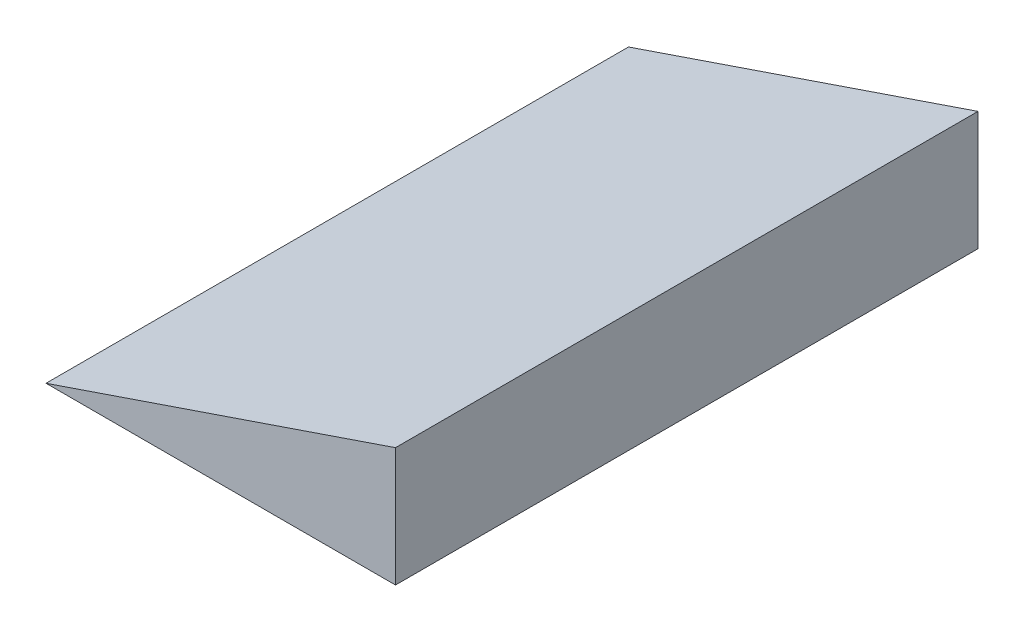
SolidWorks part; units mm, degrees
ref_plane "Front Plane" through (0, 0, 0) normal (0, 0, 1) x (1, 0, 0)
ref_plane "Top Plane" through (0, 0, 0) normal (0, 1, 0) x (1, 0, 0)
ref_plane "Right Plane" through (0, 0, 0) normal (1, 0, 0) x (0, 0, -1)
sketch "Sketch1" plane through (0, 0, 0) normal (0, 0, 1) x (1, 0, 0)
  line L0 (0, 0) -> (30, 0)
  line L1 (30, 0) -> (30, 10.2128)
  line L2 (30, 10.2128) -> (0, 0)
  dimension "D1" = 18.8
  dimension "D2" = 30
extrude "Boss-Extrude1" add sketch "Sketch1" along normal blind 50
